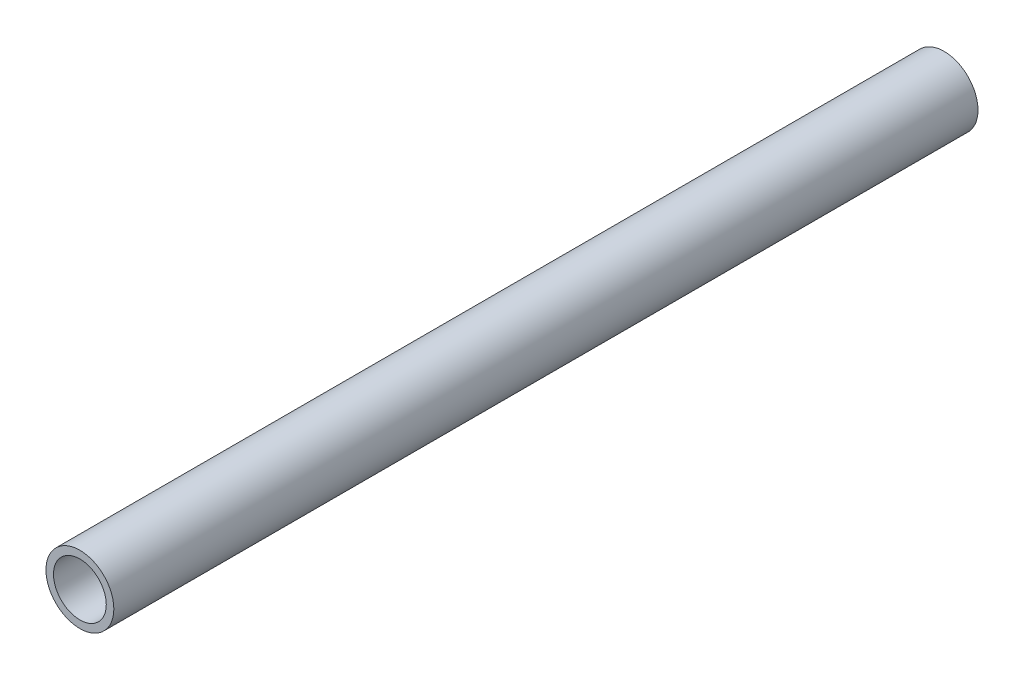
SolidWorks part; units mm, degrees
ref_plane "Front Plane" through (0, 0, 0) normal (0, 0, 1) x (1, 0, 0)
ref_plane "Top Plane" through (0, 0, 0) normal (0, 1, 0) x (1, 0, 0)
ref_plane "Right Plane" through (0, 0, 0) normal (1, 0, 0) x (0, 0, -1)
sketch "Sketch1" plane through (0, 0, 0) normal (0, 0, 1) x (1, 0, 0)
  circle A0 centre (0, 0) radius 7
  circle A1 centre (0, 0) radius 9
  dimension "D1" = 14
  dimension "D2" = 18
extrude "Boss-Extrude1" add sketch "Sketch1" along normal blind 229.14
